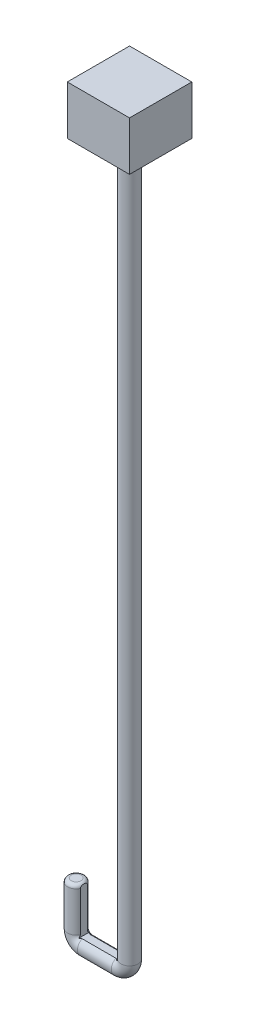
SolidWorks part; units mm, degrees
ref_plane "Alzado" through (0, 0, 0) normal (0, 0, 1) x (1, 0, 0)
ref_plane "Planta" through (0, 0, 0) normal (0, 1, 0) x (1, 0, 0)
ref_plane "Vista lateral" through (0, 0, 0) normal (1, 0, 0) x (0, 0, -1)
sketch "Croquis1" plane through (0, 0, 0) normal (0, 0, 1) x (1, 0, 0)
  line L1 (0, 0) -> (70, 0)
  line L2 (0, 0) -> (0, -55)
  line L3 (0, -55) -> (70, -55)
  line L4 (70, 0) -> (70, -55)
  dimension "D1" = 70
  dimension "D2" = 55
extrude "Saliente-Extruir1" add sketch "Croquis1" along normal blind 70
sketch "Croquis2" plane through (0, -55, 0) normal (0, -1, 0) x (1, 0, 0)
  line L0 (35, 70) -> (35, 0) construction
  line L1 (0, 70) -> (70, 70) construction
  line L2 (0, 0) -> (70, 0) construction
  circle A0 centre (35, 35) radius 9.525
  dimension "D1" = 19.05
extrude "Saliente-Extruir2" add sketch "Croquis2" along normal blind 10
sketch3d "Croquis3D2"
  line L0 (35, -65, 35) -> (35, -854, 35)
  line L1 (35, -65, 35) -> (35, -55, 35) construction
  line L2 (24, -865, 35) -> (-14, -865, 35)
  line L3 (-25, -854, 35) -> (-25, -805, 35)
  arc A0 (-14, -865, 35) -> (-25, -854, 35) centre (-14, -854, 35) ccw
  arc A1 (35, -854, 35) -> (24, -865, 35) centre (24, -854, 35) ccw
  point P8 (-25, -865, 35)
  point P9 (-14, -854, 24)
  point P12 (35, -865, 35)
  point P13 (24, -854, 24)
  dimension "D4" = 11
  dimension "D1" = 800
  dimension "D2" = 60
  dimension "D3" = 60
sketch "Croquis3" plane through (0, -65, 0) normal (0, -1, 0) x (1, 0, 0)
  circle A0 centre (35, 35) radius 9.525
  dimension "D1" = 19.05
sweep "Barrer1" add profiles "Croquis3" path "Croquis3D2"
fillet "Redondeo1" radius 4 1 edges at (-25, -805, 25.475)
sketch "Croquis5" plane through (0, 0, 0) normal (0, 0, 1) x (1, 0, 0)
  line L1 (-16.3352, -856.5214) -> (26.6417, -856.5214)
  line L2 (-16.3352, -856.5214) -> (-16.3352, -766.1092)
  line L3 (-16.3352, -766.1092) -> (26.6417, -766.1092)
  line L4 (26.6417, -856.5214) -> (26.6417, -766.1092)
extrude "Cortar-Extruir2" cut sketch "Croquis5" along normal blind 70
